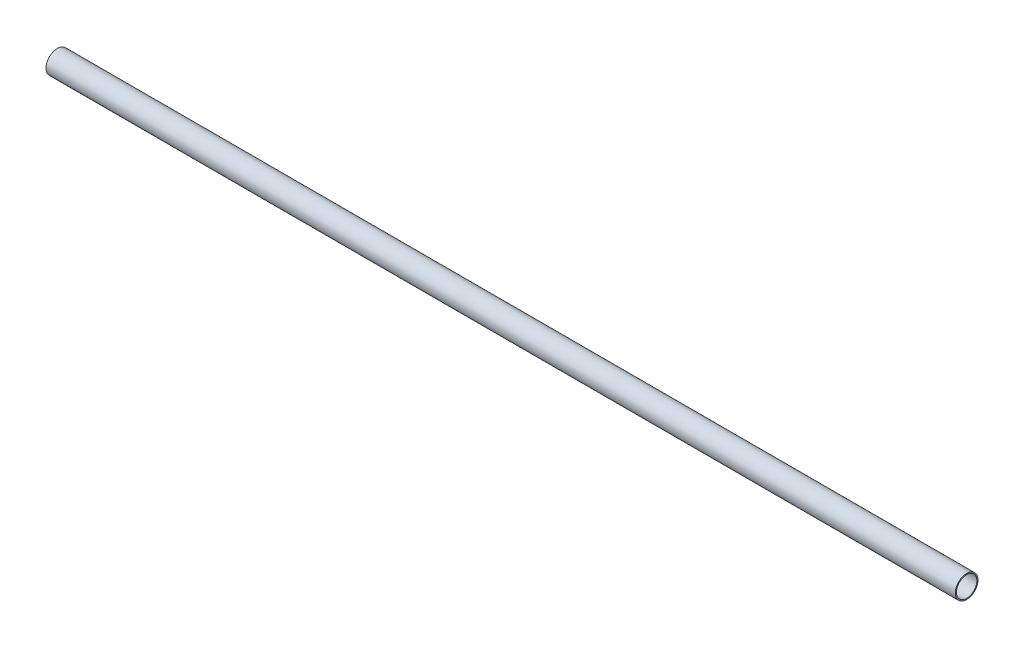
SolidWorks part; units mm, degrees
material "Thornel Mat VMA"
ref_plane "前视基准面" through (0, 0, 0) normal (0, 0, 1) x (1, 0, 0)
ref_plane "上视基准面" through (0, 0, 0) normal (0, 1, 0) x (1, 0, 0)
ref_plane "右视基准面" through (0, 0, 0) normal (1, 0, 0) x (0, 0, -1)
sketch "草图1" plane through (0, 0, 0) normal (1, 0, 0) x (0, 0, -1)
  circle A0 centre (0, 0) radius 5
  circle A1 centre (0, 0) radius 4.5
  dimension "D1" = 10
  dimension "D2" = 0.5
extrude "凸台-拉伸1" add sketch "草图1" along normal blind 400
